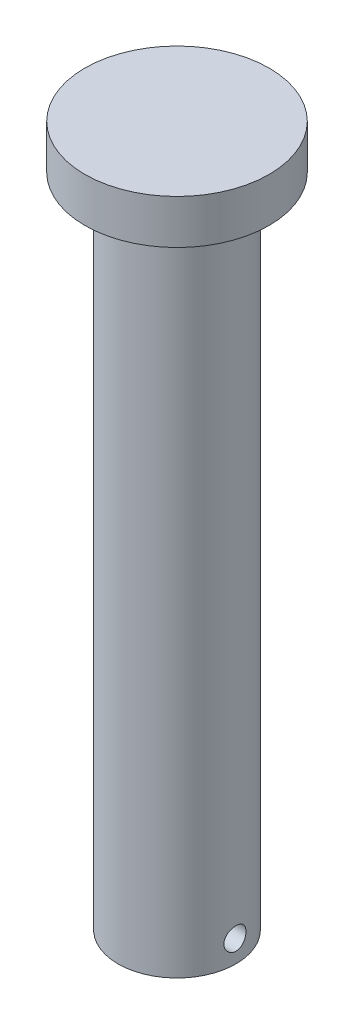
SolidWorks part; units mm, degrees
ref_plane "Front Plane" through (0, 0, 0) normal (0, 0, 1) x (1, 0, 0)
ref_plane "Top Plane" through (0, 0, 0) normal (0, 1, 0) x (1, 0, 0)
ref_plane "Right Plane" through (0, 0, 0) normal (1, 0, 0) x (0, 0, -1)
sketch "Sketch4" plane through (0, 0, 0) normal (0, 1, 0) x (1, 0, 0)
  circle A0 centre (0, 0) radius 16
extrude "Boss-Extrude9" add sketch "Sketch4" along normal blind 178
sketch "Sketch8" plane through (0, 178, 0) normal (0, 1, 0) x (1, 0, 0)
  circle A0 centre (0, 0) radius 25
extrude "Boss-Extrude10" add sketch "Sketch8" along normal blind 12
sketch "Sketch9" plane through (0, 0, 0) normal (1, 0, 0) x (0, 0, -1)
  circle A0 centre (0, 6) radius 3
extrude "Cut-Extrude1" cut sketch "Sketch9" along normal through all both and the other way through all
